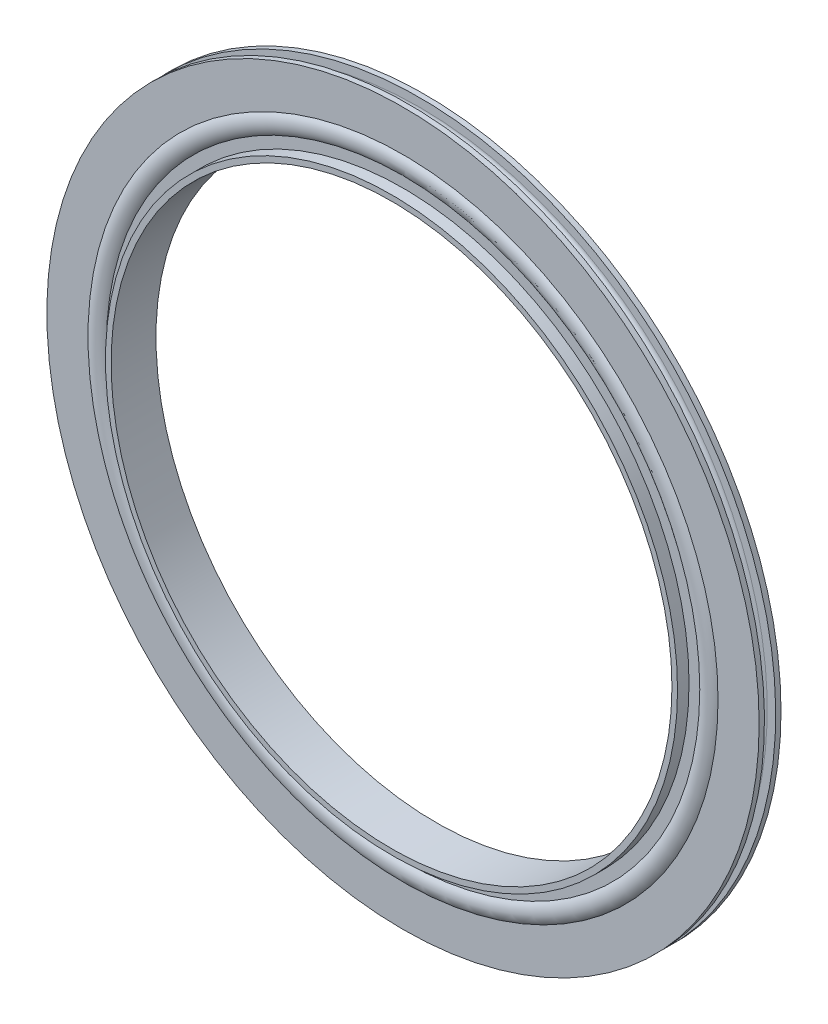
SolidWorks part; units mm, degrees
material "6061-T6 AL"
ref_plane "Front" through (0, 0, 0) normal (0, 0, 1) x (1, 0, 0)
ref_plane "Top" through (0, 0, 0) normal (0, 1, 0) x (1, 0, 0)
ref_plane "Right" through (0, 0, 0) normal (1, 0, 0) x (0, 0, -1)
sketch "Sketch1" plane through (0, 0, 0) normal (0, 0, 1) x (1, 0, 0)
  circle A0 centre (0, 0) radius 63.5
  dimension "D1" = 127
extrude "Extrude1" add sketch "Sketch1" along normal mid plane 3.9
sketch "Sketch2" plane through (0, 0, 0) normal (0, 0, 1) x (1, 0, 0)
  circle A0 centre (0, 0) radius 51
  dimension "D1" = 102
extrude "Extrude2" add sketch "Sketch2" along normal mid plane 8
sketch "Sketch3" plane through (0, 0, 4) normal (0, 0, 1) x (1, 0, 0)
  circle A0 centre (0, 0) radius 50
  dimension "D1" = 100
extrude "Extrude3" cut sketch "Sketch3" against normal through all
sketch "Sketch5" plane through (0, 0, 0) normal (1, 0, 0) x (0, 0, -1)
  line L0 (-1.95, 51) -> (-4, 51) construction
  line L1 (-4, 0) -> (4, 0) construction
  line L2 (-4, 51) -> (-4, -51) construction
  line L3 (4, -51) -> (4, 51) construction
  circle A0 centre (0, 54.54) radius 2.54
  dimension "D1" = 5.08
  dimension "D2" = 1
revolve "Revolve2" add sketch "Sketch5" angle 360 about L1
sketch "Sketch6" plane through (0, 0, 0) normal (1, 0, 0) x (0, 0, -1)
  line L0 (-1, 63.5) -> (-1, 62)
  line L1 (1.95, 63.5) -> (-1.95, 63.5) construction
  line L2 (1, 62) -> (1, 63.5)
  line L3 (1, 63.5) -> (-1, 63.5)
  line L4 (-4, 0) -> (4, 0) construction
  line L5 (-4, 51) -> (-4, -51) construction
  line L6 (4, -51) -> (4, 51) construction
  arc A0 (-1, 62) -> (1, 62) centre (0, 62) ccw
  dimension "D1" = 2
  dimension "D2" = 2.5
revolve "Cut-Revolve1" cut sketch "Sketch6" angle 360 about L4
